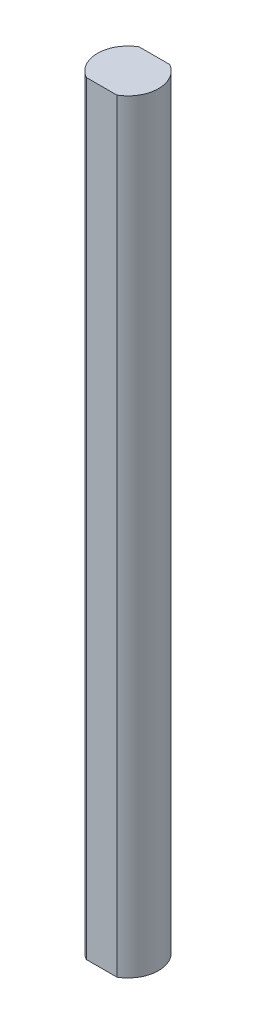
SolidWorks part; units mm, degrees
ref_plane "Front Plane" through (0, 0, 0) normal (0, 0, 1) x (1, 0, 0)
ref_plane "Top Plane" through (0, 0, 0) normal (0, 1, 0) x (1, 0, 0)
ref_plane "Right Plane" through (0, 0, 0) normal (1, 0, 0) x (0, 0, -1)
sketch "Sketch2" plane through (0, 0, 0) normal (0, 1, 0) x (1, 0, 0)
  line L1 (-2, -3.4641) -> (2, -3.4641)
  line L2 (-2, -3.4641) -> (-2, 3.4641) construction
  line L3 (-2, 3.4641) -> (2, 3.4641)
  line L4 (2, -3.4641) -> (2, 3.4641) construction
  line L5 (-2, -3.4641) -> (2, 3.4641) construction
  line L6 (-2, 3.4641) -> (2, -3.4641) construction
  arc A0 (-2, 3.4641) -> (-2, -3.4641) centre (0, 0) ccw
  arc A1 (2, -3.4641) -> (2, 3.4641) centre (0, 0) ccw
  dimension "D1" = 8
  dimension "D2" = 4
extrude "Boss-Extrude1" add sketch "Sketch2" along normal mid plane 100
